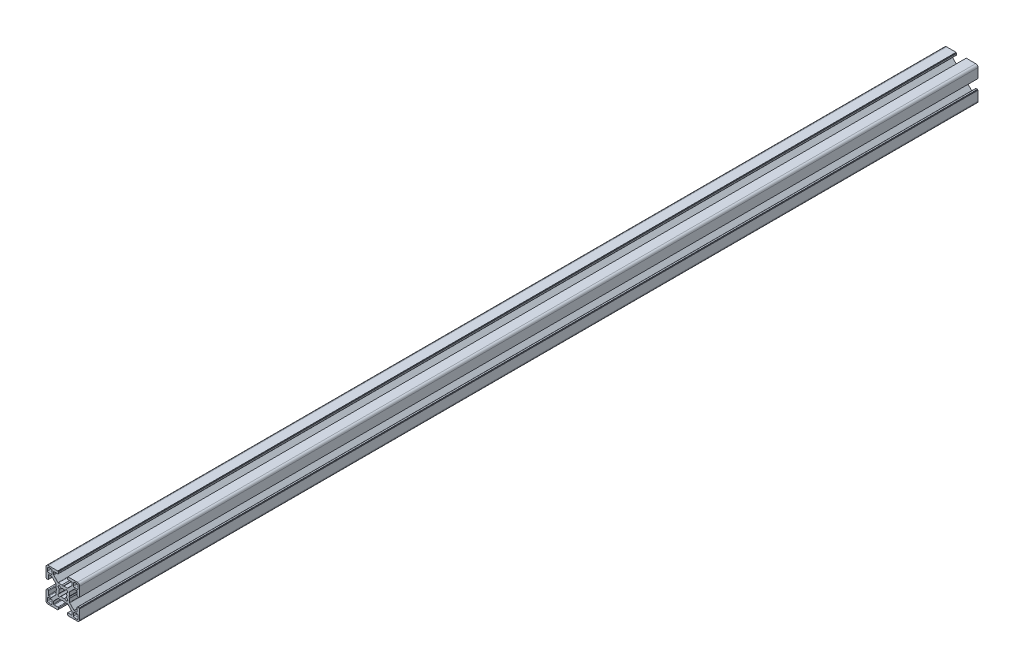
SolidWorks part; units mm, degrees
ref_plane "Front Plane" through (0, 0, 0) normal (0, 0, 1) x (1, 0, 0)
ref_plane "Top Plane" through (0, 0, 0) normal (0, 1, 0) x (1, 0, 0)
ref_plane "Right Plane" through (0, 0, 0) normal (1, 0, 0) x (0, 0, -1)
sketch "Sketch1" plane through (0, 0, 0) normal (0, 0, 1) x (1, 0, 0)
  line L0 (-15, 0) -> (15, 0) construction
  line L1 (0, -15) -> (0, 15) construction
  line L2 (-4.5, 15) -> (4.5, 15) construction
  line L3 (-4, -15) -> (4, -15) construction
  line L4 (-4.5, 15) -> (-4.5, 14.5)
  line L5 (-4.5, 14.5) -> (-4, 14.5)
  line L6 (-4, 14.5) -> (-4, 13.29)
  line L7 (-4.5, 12.79) -> (-7.7675, 12.79)
  line L8 (-8.2675, 12.29) -> (-8.2675, 10.2707)
  line L9 (-8.1211, 9.9171) -> (-4.3504, 6.1464)
  line L10 (-3.9968, 6) -> (0, 6)
  line L11 (0, 0) -> (-15, 15) construction
  line L12 (-4.5, 15) -> (-12.968, 15)
  line L14 (-12.705, 9.5135) -> (-10.5135, 9.5135)
  line L15 (-13.705, 10.5135) -> (-13.705, 12.705)
  line L16 (-12.705, 13.705) -> (-10.5135, 13.705)
  line L17 (-9.5135, 10.5135) -> (-9.5135, 12.705)
  line L18 (-13.705, 9.5135) -> (-9.5135, 13.705) construction
  line L19 (-13.705, 13.705) -> (-9.5135, 9.5135) construction
  line L20 (-3.1568, 4.5038) -> (-1.5303, 3.1477) construction
  line L21 (-4.5038, 3.1568) -> (-3.1477, 1.5303) construction
  line L22 (-6, 3.9968) -> (-6, 0)
  line L23 (-9.9171, 8.1211) -> (-6.1464, 4.3504)
  line L24 (-15, 4.5) -> (-15, 12.968)
  line L25 (-12.29, 8.2675) -> (-10.2707, 8.2675)
  line L26 (-12.79, 4.5) -> (-12.79, 7.7675)
  line L27 (-14.5, 4) -> (-13.29, 4)
  line L28 (-14.5, 4.5) -> (-14.5, 4)
  line L29 (-15, 4.5) -> (-14.5, 4.5)
  circle A0 centre (0, 0) radius 3.5
  arc A1 (-12.968, 15) -> (-15, 12.968) centre (-12.968, 12.968) ccw
  circle A2 centre (0, 0) radius 5.5 construction
  arc A3 (-10.5135, 9.5135) -> (-9.5135, 10.5135) centre (-10.5135, 10.5135) ccw
  arc A4 (-13.705, 12.705) -> (-12.705, 13.705) centre (-12.705, 12.705) cw
  arc A5 (-10.5135, 13.705) -> (-9.5135, 12.705) centre (-10.5135, 12.705) cw
  arc A6 (-12.705, 9.5135) -> (-13.705, 10.5135) centre (-12.705, 10.5135) cw
  arc A7 (-12.79, 4.5) -> (-13.29, 4) centre (-13.29, 4.5) cw
  arc A8 (-12.29, 8.2675) -> (-12.79, 7.7675) centre (-12.29, 7.7675) ccw
  arc A9 (-9.9171, 8.1211) -> (-10.2707, 8.2675) centre (-10.2707, 7.7675) ccw
  arc A10 (-6, 3.9968) -> (-6.1464, 4.3504) centre (-6.5, 3.9968) ccw
  arc A11 (-4.3504, 6.1464) -> (-3.9968, 6) centre (-3.9968, 6.5) ccw
  arc A12 (-4, 13.29) -> (-4.5, 12.79) centre (-4.5, 13.29) cw
  arc A13 (-7.7675, 12.79) -> (-8.2675, 12.29) centre (-7.7675, 12.29) ccw
  arc A14 (-8.2675, 10.2707) -> (-8.1211, 9.9171) centre (-7.7675, 10.2707) ccw
  point P4 (0, 0)
  point P8 (0, 0)
  point P13 (0, 15)
  point P15 (0, -15)
  point P16 (0, 6)
  point P23 (-11.6092, 11.6093)
  point P26 (0, 6)
  point P62 (-12.79, 4)
  point P65 (-12.79, 8.2675)
  point P68 (-10.0636, 8.2675)
  point P71 (-6, 4.2039)
  point P74 (-4.2039, 6)
  point P77 (-4, 12.79)
  point P80 (-8.2675, 12.79)
  point P83 (-8.2675, 10.0636)
  dimension "Center Hole Diameter" = 7
  dimension "D11" = 2.032
  dimension "D9" = 11
  dimension "D13" = 1
  dimension "D14" = 0.5
  dimension "Rail Height" = 30
  dimension "Rail Width" = 30
  dimension "T-Slot Width" = 8
  dimension "T-Slot Depth" = 9
  dimension "D1" = 9
  dimension "D2" = 45
  dimension "D3" = 8
  dimension "D4" = 2.21
  dimension "D5" = 16.535
  dimension "D7" = 2.54
  dimension "D6" = 1.295
  dimension "D8" = 1.246
  dimension "D10" = 10.36
  dimension "D12" = 1.905
sketch "Sketch2" plane through (0, 0, 0) normal (1, 0, 0) x (0, 0, -1)
  line L0 (-76.2, 0) -> (76.2, 0) construction
  line L2 (0, -15) -> (0, 15) construction
  line L3 (0, -15) -> (0, 15) construction
  line L4 (-76.2, -15) -> (-76.2, 15) construction
  line L5 (76.2, -15) -> (76.2, 15) construction
  point P0 (-38.7, 0)
  point P3 (0, 0)
  point P4 (38.7, 0)
  point P12 (-76.2, 0)
  point P14 (76.2, 0)
  dimension "Length" = 152.4
  dimension "D1" = 37.5
sketch "Sketch3" plane through (0, 0, 0) normal (0, 0, 1) x (1, 0, 0)
  line L0 (-4.5038, 3.1568) -> (-3.1477, 1.5303)
  line L1 (0, 3.5) -> (0, 5.5)
  line L2 (-5.5, 0) -> (-3.5, 0)
  line L7 (-6, 3.9968) -> (-6, 0) construction
  line L31 (-9.9171, 8.1211) -> (-6.1464, 4.3504) construction
  line L117 (-12.29, 8.2675) -> (-10.2707, 8.2675) construction
  line L118 (-12.79, 4.5) -> (-12.79, 7.7675) construction
  line L157 (-12.705, 9.5135) -> (-10.5135, 9.5135)
  line L158 (-9.5135, 10.5135) -> (-9.5135, 12.705)
  line L163 (-10.5135, 13.705) -> (-12.705, 13.705)
  line L164 (-13.705, 12.705) -> (-13.705, 10.5135)
  line L165 (-12.705, 9.5135) -> (-10.5135, 9.5135)
  line L166 (-9.5135, 10.5135) -> (-9.5135, 12.705)
  line L167 (-10.5135, 13.705) -> (-12.705, 13.705)
  line L168 (-13.705, 12.705) -> (-13.705, 10.5135)
  line L169 (-14.5, 4) -> (-13.29, 4) construction
  line L170 (-14.5, 4.5) -> (-14.5, 4) construction
  line L171 (-15, 4.5) -> (-14.5, 4.5) construction
  line L172 (-15, 4.5) -> (-15, 12.968) construction
  line L173 (-4.5, 15) -> (-12.968, 15) construction
  line L174 (-4.5, 15) -> (-4.5, 14.5) construction
  line L175 (-4.5, 14.5) -> (-4, 14.5) construction
  line L176 (-4, 14.5) -> (-4, 13.29) construction
  line L177 (-4.5, 12.79) -> (-7.7675, 12.79) construction
  line L178 (-8.2675, 12.29) -> (-8.2675, 10.2707) construction
  line L179 (-8.1211, 9.9171) -> (-4.3504, 6.1464) construction
  line L180 (-3.9968, 6) -> (0, 6) construction
  line L181 (-6, 3.9968) -> (-6, 0.866)
  line L182 (-9.9171, 8.1211) -> (-6.1464, 4.3504)
  line L183 (-12.29, 8.2675) -> (-10.2707, 8.2675)
  line L184 (-12.79, 4.5) -> (-12.79, 7.7675)
  line L185 (-14.5, 4) -> (-13.29, 4)
  line L186 (-14.5, 4.5) -> (-14.5, 4)
  line L187 (-15, 4.5) -> (-14.5, 4.5)
  line L188 (-15, 4.5) -> (-15, 12.968)
  line L189 (-4.5, 15) -> (-12.968, 15)
  line L190 (-4.5, 15) -> (-4.5, 14.5)
  line L191 (-4.5, 14.5) -> (-4, 14.5)
  line L192 (-4, 14.5) -> (-4, 13.29)
  line L193 (-4.5, 12.79) -> (-7.7675, 12.79)
  line L194 (-8.2675, 12.29) -> (-8.2675, 10.2707)
  line L195 (-8.1211, 9.9171) -> (-4.3504, 6.1464)
  line L196 (-3.9968, 6) -> (-0.866, 6)
  line L197 (-0.866, 6) -> (0, 5.5)
  line L198 (0, -15) -> (0, 15) construction
  line L199 (0, 0) -> (-15, 15) construction
  line L200 (0, 0) -> (-15, 15) construction
  line L201 (-3.1568, 4.5038) -> (-1.5303, 3.1477) construction
  line L202 (-3.1568, 4.5038) -> (-1.5303, 3.1477)
  line L203 (-6, 0.866) -> (-5.5, 0)
  line L204 (-15, 0) -> (15, 0) construction
  line L205 (-15, 0) -> (15, 0) construction
  line L206 (0, -15) -> (0, 15) construction
  arc A0 (-3.5, 0) -> (-3.1477, 1.5303) centre (0, 0) cw
  arc A10 (-6, 3.9968) -> (-6.1464, 4.3504) centre (-6.5, 3.9968) ccw construction
  circle A16 centre (0, 0) radius 3.5
  arc A18 (0, 3.5) -> (-1.5303, 3.1477) centre (0, 0) ccw
  arc A20 (-9.9171, 8.1211) -> (-10.2707, 8.2675) centre (-10.2707, 7.7675) ccw construction
  arc A22 (-12.29, 8.2675) -> (-12.79, 7.7675) centre (-12.29, 7.7675) ccw construction
  arc A28 (-13.29, 4) -> (-12.79, 4.5) centre (-13.29, 4.5) ccw construction
  arc A29 (-10.5135, 9.5135) -> (-9.5135, 10.5135) centre (-10.5135, 10.5135) ccw
  arc A30 (-9.5135, 12.705) -> (-10.5135, 13.705) centre (-10.5135, 12.705) ccw
  arc A31 (-12.705, 13.705) -> (-13.705, 12.705) centre (-12.705, 12.705) ccw
  arc A32 (-13.705, 10.5135) -> (-12.705, 9.5135) centre (-12.705, 10.5135) ccw
  arc A33 (-10.5135, 9.5135) -> (-9.5135, 10.5135) centre (-10.5135, 10.5135) ccw
  arc A34 (-9.5135, 12.705) -> (-10.5135, 13.705) centre (-10.5135, 12.705) ccw
  arc A35 (-12.705, 13.705) -> (-13.705, 12.705) centre (-12.705, 12.705) ccw
  arc A36 (-13.705, 10.5135) -> (-12.705, 9.5135) centre (-12.705, 10.5135) ccw
  arc A37 (-12.968, 15) -> (-15, 12.968) centre (-12.968, 12.968) ccw construction
  arc A38 (-4.5, 12.79) -> (-4, 13.29) centre (-4.5, 13.29) ccw construction
  arc A39 (-7.7675, 12.79) -> (-8.2675, 12.29) centre (-7.7675, 12.29) ccw construction
  arc A40 (-8.2675, 10.2707) -> (-8.1211, 9.9171) centre (-7.7675, 10.2707) ccw construction
  arc A41 (-4.3504, 6.1464) -> (-3.9968, 6) centre (-3.9968, 6.5) ccw construction
  arc A42 (-6, 3.9968) -> (-6.1464, 4.3504) centre (-6.5, 3.9968) ccw
  arc A43 (-9.9171, 8.1211) -> (-10.2707, 8.2675) centre (-10.2707, 7.7675) ccw
  arc A44 (-12.29, 8.2675) -> (-12.79, 7.7675) centre (-12.29, 7.7675) ccw
  arc A45 (-13.29, 4) -> (-12.79, 4.5) centre (-13.29, 4.5) ccw
  arc A46 (-12.968, 15) -> (-15, 12.968) centre (-12.968, 12.968) ccw
  arc A47 (-4.5, 12.79) -> (-4, 13.29) centre (-4.5, 13.29) ccw
  arc A48 (-7.7675, 12.79) -> (-8.2675, 12.29) centre (-7.7675, 12.29) ccw
  arc A49 (-8.2675, 10.2707) -> (-8.1211, 9.9171) centre (-7.7675, 10.2707) ccw
  arc A50 (-4.3504, 6.1464) -> (-3.9968, 6) centre (-3.9968, 6.5) ccw
  circle A51 centre (0, 0) radius 5.5 construction
  arc A52 (-3.1568, 4.5038) -> (-4.5038, 3.1568) centre (0, 0) ccw
  dimension "D3" = 60
  dimension "D4" = 60
  dimension "D1" = 0
  dimension "D2" = 0
extrude "Boss-Extrude1" add sketch "Sketch3" along normal mid plane 800
pattern_circular "CirPattern1" count 4 over 360 about axis through (0, 0, 0) along (0, 0, 1) of "Boss-Extrude1"
ref_plane "Contact Plane1" through (15, 0, 0) normal (1, 0, 0) x (0, 0, -1)
ref_plane "Contact Plane2" through (0, -15, 0) normal (0, 1, 0) x (1, 0, 0)
ref_plane "Contact Plane3" through (-15, 0, 0) normal (1, 0, 0) x (0, 0, -1)
ref_plane "Contact Plane4" through (0, 15, 0) normal (0, 1, 0) x (1, 0, 0)
equation "\"D1@Sketch2\" = \"Rail Height@Sketch1\" * 1.25"
equation "\"D1@Sketch1\"=\"T-Slot Width@Sketch1\"+1mm"
equation "\"D3@Sketch1\"=\"T-Slot Width@Sketch1\""
equation "\"D1@Boss-Extrude1\"=\"Length\""
equation "\"Length\"= 800mm"
